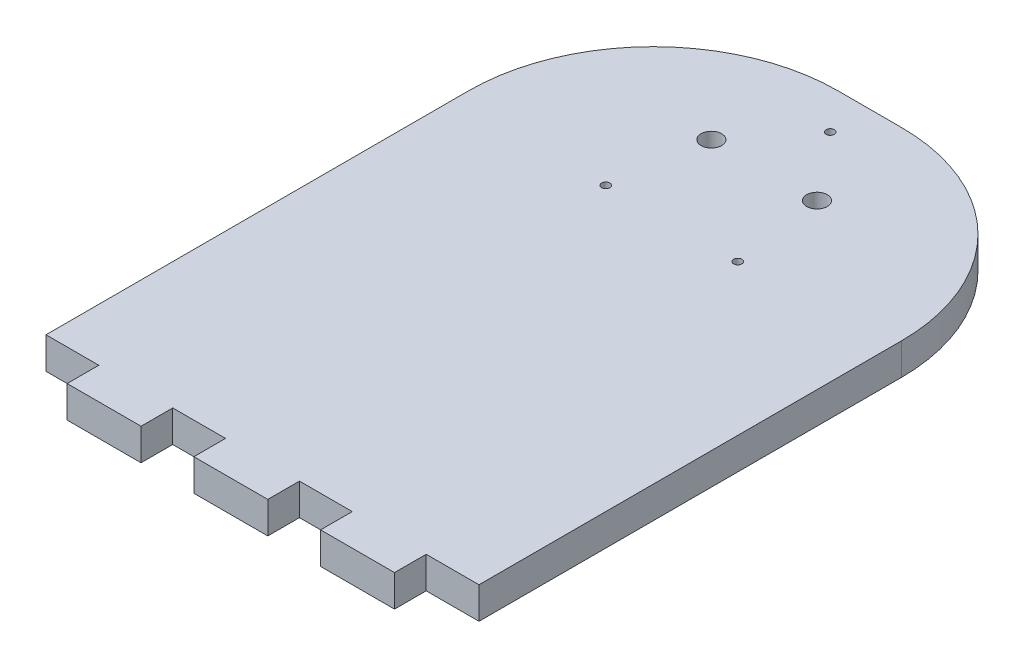
SolidWorks part; units mm, degrees
ref_plane "Alzado" through (0, 0, 0) normal (0, 0, 1) x (1, 0, 0)
ref_plane "Planta" through (0, 0, 0) normal (0, 1, 0) x (1, 0, 0)
ref_plane "Vista lateral" through (0, 0, 0) normal (1, 0, 0) x (0, 0, -1)
sketch "Croquis1" plane through (0, 0, 0) normal (0, 1, 0) x (1, 0, 0)
  line L0 (0, 0) -> (20, 0)
  line L1 (164, 230) -> (0, 230)
  line L2 (0, 230) -> (0, 0)
  line L3 (48, 0) -> (68, 0)
  line L4 (164, 230) -> (164, 0)
  line L6 (20, 0) -> (20, -12)
  line L7 (20, -12) -> (48, -12)
  line L8 (48, 0) -> (48, -12)
  line L9 (68, 0) -> (68, -12)
  line L10 (68, -12) -> (96, -12)
  line L11 (96, 0) -> (96, -12)
  line L12 (116, 0) -> (116, -12)
  line L13 (116, -12) -> (144, -12)
  line L14 (144, 0) -> (144, -12)
  line L15 (96, 0) -> (116, 0)
  line L16 (144, 0) -> (164, 0)
  dimension "D1" = 20
  dimension "D2" = 20
  dimension "D3" = 20
  dimension "D4" = 20
  dimension "D15" = 12
  dimension "D16" = 28
  dimension "D17" = 12
  dimension "D18" = 12
  dimension "D19" = 28
  dimension "D20" = 12
  dimension "D21" = 12
  dimension "D22" = 28
  dimension "D23" = 230
  dimension "D29" = 0
extrude "Saliente-Extruir1" add sketch "Croquis1" along normal blind 12 contours L1 L2 L0 L6 L7 L8 L3 L9 L10 L11 L15 L12 L13 L14 L16 L4
sketch "Croquis2" plane through (0, 12, 0) normal (0, 1, 0) x (1, 0, 0)
  line L0 (82, 233.5651) -> (82, 134.0684) construction
  line L1 (0, 230) -> (0, 0) construction
  line L2 (164, 230) -> (164, 0) construction
  line L3 (48, 0) -> (68, 0) construction
  line L4 (96, 0) -> (116, 0) construction
  circle A0 centre (82, 215) radius 1.55
  circle A1 centre (57, 155) radius 1.55
  circle A2 centre (107, 155) radius 1.55
  circle A3 centre (62, 190) radius 3.9
  circle A4 centre (102, 190) radius 3.9
  dimension "D2" = 7.8
  dimension "D3" = 7.8
  dimension "D4" = 3.1
  dimension "D5" = 3.1
  dimension "D6" = 3.1
  dimension "D16" = 190
  dimension "D17" = 190
  dimension "D1" = 40
  dimension "D7" = 25
  dimension "D8" = 35
  dimension "D9" = 35
  dimension "D10" = 50
  dimension "D11" = 25
  dimension "D12" = 20
  dimension "D13" = 0
  dimension "D14" = 82
  dimension "D15" = 82
extrude "Cortar-Extruir1" cut sketch "Croquis2" against normal up to surface (12 mm away) up to face at (82, 0, -24.25)
fillet "Redondeo1" radius 70 2 edges at (164, 6, -230) (0, 6, -230)
